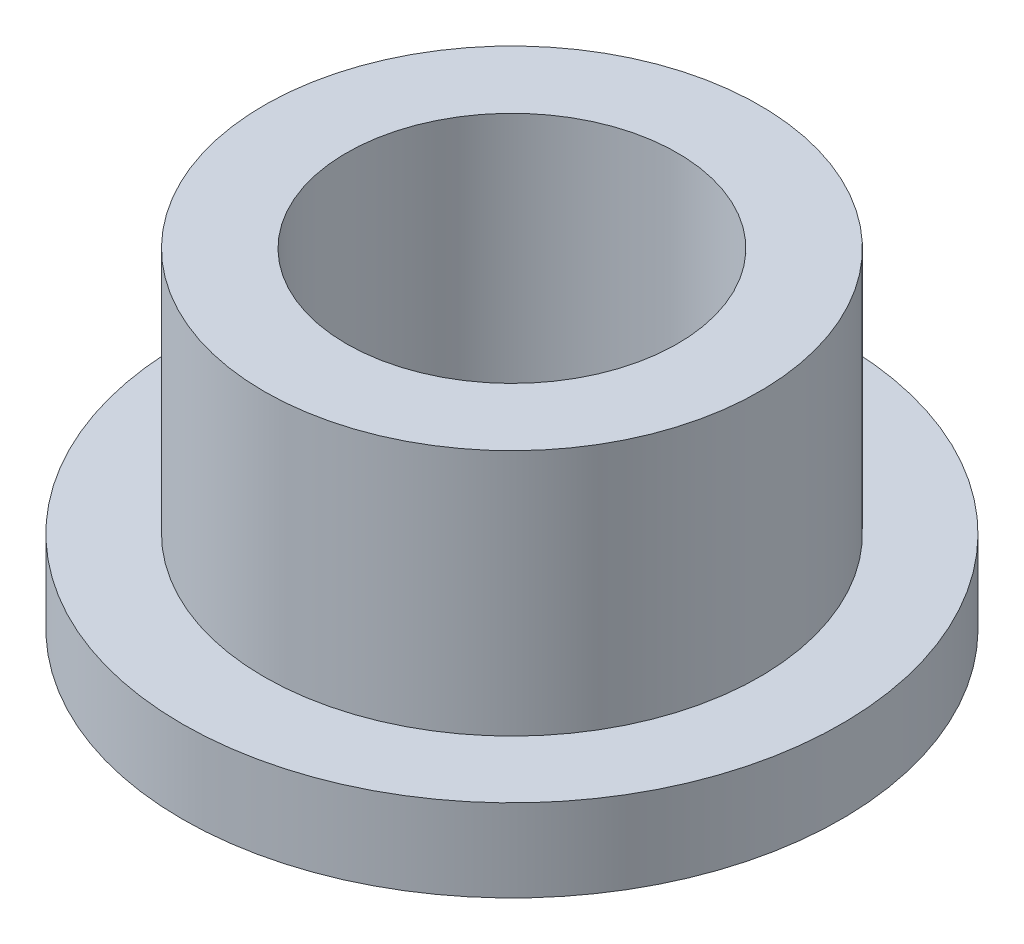
SolidWorks part; units mm, degrees
ref_plane "Front" through (0, 0, 0) normal (0, 0, 1) x (1, 0, 0)
ref_plane "Top" through (0, 0, 0) normal (0, 1, 0) x (1, 0, 0)
ref_plane "Right" through (0, 0, 0) normal (1, 0, 0) x (0, 0, -1)
sketch "Sketch1" plane through (0, 0, 0) normal (0, 1, 0) x (1, 0, 0)
  circle A0 centre (0, 0) radius 3.1877
  circle A1 centre (0, 0) radius 4.7752
  circle A2 centre (0, 0) radius 6.35
  dimension "ID" = 6.3754
  dimension "OD" = 9.5504
  dimension "FlangeOD" = 12.7
sketch "Sketch2" plane through (0, 0, 0) normal (0, 1, 0) x (1, 0, 0)
  circle A0 centre (0, 0) radius 3.1877 construction
  circle A1 centre (0, 0) radius 4.7752 construction
  circle A2 centre (0, 0) radius 3.1877
  circle A3 centre (0, 0) radius 4.7752
extrude "Boss-Extrude1" add sketch "Sketch2" along normal blind 6.35
sketch "Sketch3" plane through (0, 0, 0) normal (0, 1, 0) x (1, 0, 0)
  circle A0 centre (0, 0) radius 6.35 construction
  circle A1 centre (0, 0) radius 4.7752 construction
  circle A2 centre (0, 0) radius 6.35
  circle A3 centre (0, 0) radius 4.7752
extrude "Boss-Extrude2" add sketch "Sketch3" along normal blind 1.5875
